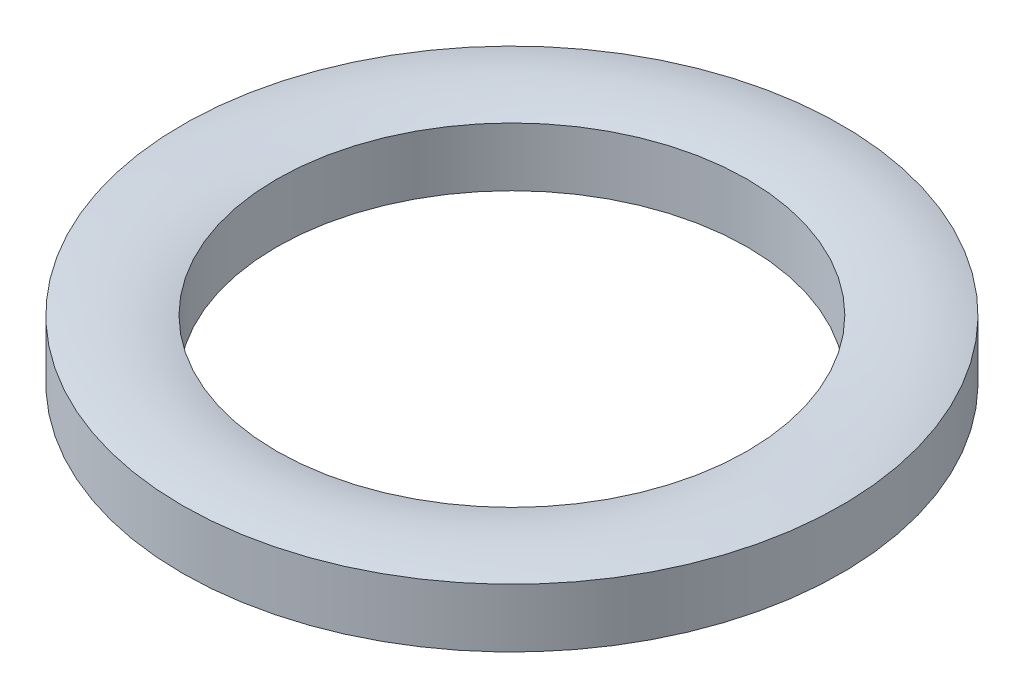
SolidWorks part; units mm, degrees
ref_plane "Plane1" through (0, 0, 0) normal (0, 0, 1) x (1, 0, 0)
ref_plane "Plane2" through (0, 0, 0) normal (0, 1, 0) x (1, 0, 0)
ref_plane "Plane3" through (0, 0, 0) normal (1, 0, 0) x (0, 0, -1)
revolve "Base-Revolve" add sketch "Sketch1" angle 360 about L0
sketch "Sketch1" plane through (0, 0, 0) normal (0, 0, 1) x (1, 0, 0)
  line L0 (0, 10.2161) -> (0, -9.1945) construction
  line L1 (6, 0) -> (-4.9843, 0) construction
  line L4 (5, 0.127) -> (5, 1.373)
  line L6 (7, 1.373) -> (7, 0.127)
  arc A0 (5, 1.373) -> (7, 1.373) centre (6, -2.5) cw
  arc A1 (5, 0.127) -> (7, 0.127) centre (6, 4) ccw
  dimension "r" = 4
  dimension "_d" = 10
  dimension "t" = 1.5
  dimension "_dd" = 14
